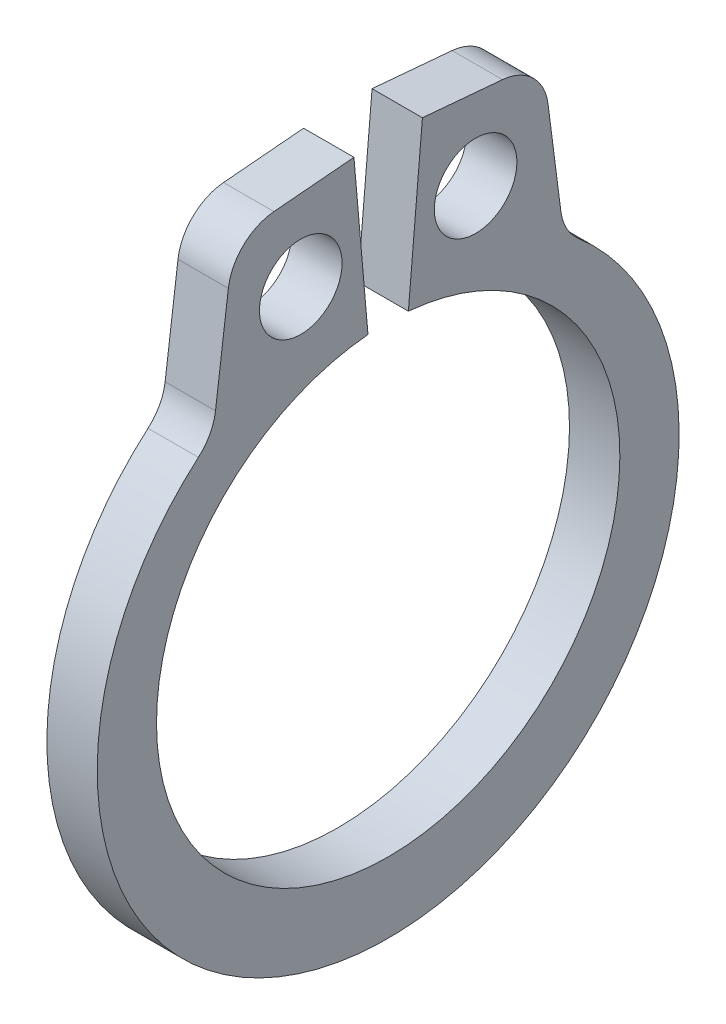
SolidWorks part; units mm, degrees
material "Cast Carbon Steel"
ref_plane "Front" through (0, 0, 0) normal (0, 0, 1) x (1, 0, 0)
ref_plane "Top" through (0, 0, 0) normal (0, 1, 0) x (1, 0, 0)
ref_plane "Right" through (0, 0, 0) normal (1, 0, 0) x (0, 0, -1)
sketch "Sketch1" plane through (0, 0, 0) normal (1, 0, 0) x (0, 0, -1)
  line L0 (0, 0) -> (0, 2.921) construction
  line L1 (-0.2546, 2.9099) -> (-0.4317, 4.9342)
  line L2 (0.4317, 4.9342) -> (1.9499, 4.8013)
  line L3 (1.9499, 4.8013) -> (2.2098, 2.786)
  line L4 (0.2546, 2.9099) -> (0.4317, 4.9342)
  line L5 (-0.4317, 4.9342) -> (-1.9499, 4.8013)
  line L6 (-1.9499, 4.8013) -> (-2.2098, 2.786)
  line L7 (-2.2098, 2.786) -> (-1.8152, 2.2885) construction
  line L8 (2.2098, 2.786) -> (1.8152, 2.2885) construction
  line L9 (0, -2.921) -> (0, -3.81) construction
  line L10 (-1.9499, 4.8013) -> (-0.2546, 2.9099) construction
  line L11 (0, 2.921) -> (0, 4.953) construction
  line L12 (-2.921, 0) -> (2.921, 0) construction
  circle A0 centre (0, 0) radius 2.921 construction
  arc A1 (-0.2546, 2.9099) -> (0.2546, 2.9099) centre (0, 0) ccw
  circle A3 centre (0, 0) radius 5.461 construction
  circle A4 centre (-1.1022, 3.8556) radius 0.5207
  circle A5 centre (1.1022, 3.8556) radius 0.5207
  arc A6 (-2.2098, 2.786) -> (2.2098, 2.786) centre (0, -0.1418) ccw
  point P0 (0, -3.81)
  dimension "A" = 5.842
  dimension "Hole" = 1.0414
  dimension "Smin" = 0.635
  dimension "H" = 2.032
  dimension "D2" = 1.524
  dimension "Angle" = 5
extrude "Extrude1" add sketch "Sketch1" along normal mid plane 0.635
fillet "Fillet1" radius 0.635 4 edges at (0, 2.786, 2.2098) (0, 2.786, -2.2098) (0, 4.8013, 1.9499) (0, 4.8013, -1.9499)
sketch "Sketch2" plane through (0, 0, 0) normal (0, 0, 1) x (1, 0, 0)
  line L0 (-3.5433, 0) -> (9.1567, 0)
  line L1 (9.1567, 0) -> (9.1567, -3.175)
  line L2 (-0.3683, -3.175) -> (-3.2893, -3.175)
  line L3 (9.1567, -3.175) -> (0.3683, -3.175)
  line L4 (0.3683, -3.175) -> (0.3683, -2.921)
  line L5 (0.3683, -2.921) -> (-0.3683, -2.921)
  line L6 (-0.3683, -2.921) -> (-0.3683, -3.175)
  line L7 (-0.3683, -3.175) -> (-3.5433, -3.175) construction
  line L8 (-3.5433, -3.175) -> (-3.5433, 0) construction
  line L9 (9.1567, 0) -> (76.391, 0) construction
  line L10 (-3.2893, -3.175) -> (-3.5433, -2.921)
  line L11 (-3.5433, -2.921) -> (-3.5433, 0)
  point P10 (0, -2.921)
  dimension "D2" = 12.7
  dimension "D3" = 3.175
  dimension "D1" = 45
revolve "Revolve1" [suppressed] add sketch "Sketch2" angle 360 about L9
delete or keep bodies "Body-Delete1" [suppressed] type delete bodies bodies 122
equation "\"D2@Sketch2\" = \"D1@Extrude1\"*20"
equation "\"D3@Sketch2\" = \"D2@Sketch2\"/4"
equation "\"D2@Sketch1\" = \"H@Sketch1\"*.75"
